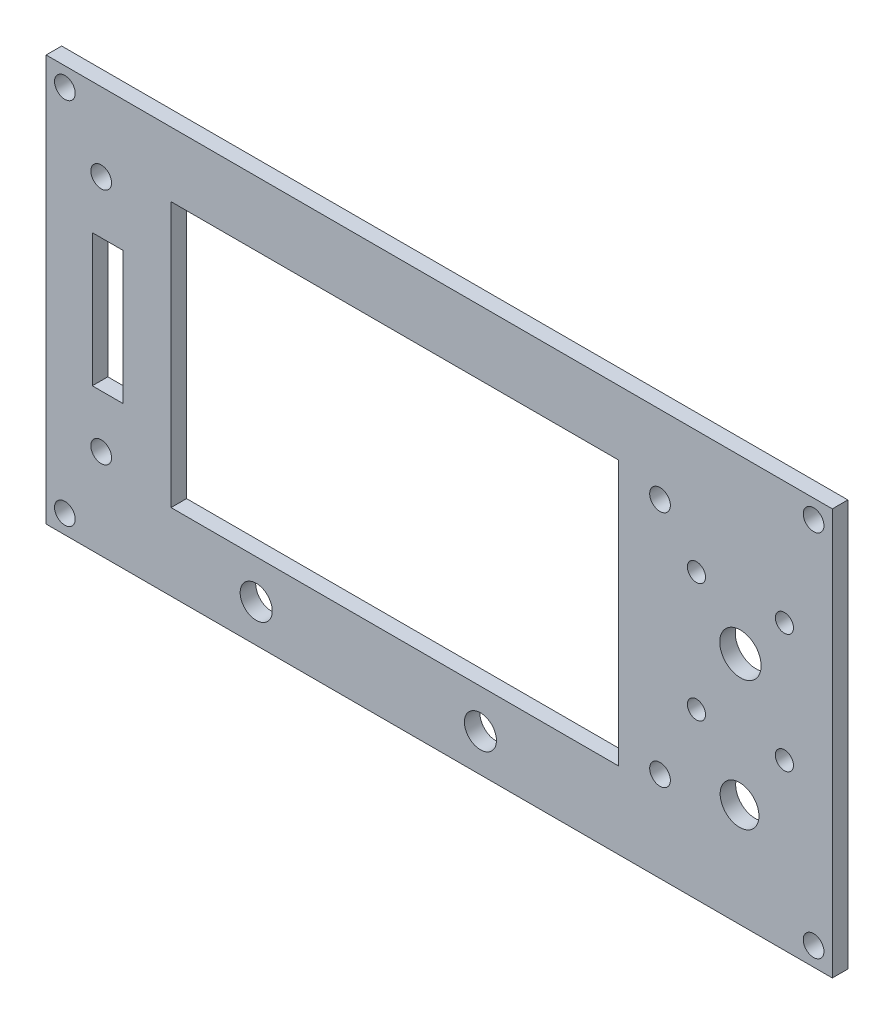
SolidWorks part; units mm, degrees
ref_plane "Plan de face" through (0, 0, 0) normal (0, 0, 1) x (1, 0, 0)
ref_plane "Plan de dessus" through (0, 0, 0) normal (0, 1, 0) x (1, 0, 0)
ref_plane "Plan de droite" through (0, 0, 0) normal (1, 0, 0) x (0, 0, -1)
sketch "Esquisse1" plane through (0, 0, -2.2) normal (0, 0, 1) x (1, 0, 0)
  line L0 (-15.1944, 26.9214) -> (-95.1944, 26.9214) construction
  line L1 (-119.8323, 39.9055) -> (32.1075, 39.9055)
  line L2 (-119.8323, 39.9055) -> (-119.8323, -38.6114)
  line L3 (-119.8323, -38.6114) -> (32.1075, -38.6114)
  line L4 (32.1075, 39.9055) -> (32.1075, -38.6114)
  line L5 (-95.6944, 27.4214) -> (-9.1944, 27.4214)
  line L6 (-95.6944, 27.4214) -> (-95.6944, -23.7786)
  line L7 (-95.6944, -23.7786) -> (-9.1944, -23.7786)
  line L8 (-9.1944, 27.4214) -> (-9.1944, -23.7786)
  line L9 (-95.1944, 26.9214) -> (-95.1944, -23.2786) construction
  line L10 (-15.1944, -23.2786) -> (-15.1944, 26.9214) construction
  line L11 (-95.1944, -23.2786) -> (-15.1944, -23.2786) construction
  line L12 (-112.5896, 39.9055) -> (-119.8323, 32.6629) construction
  line L13 (-110.9137, 14.6275) -> (-104.9761, 14.6275)
  line L14 (-110.9137, 14.6275) -> (-110.9137, -11.0054)
  line L15 (-110.9137, -11.0054) -> (-104.9761, -11.0054)
  line L16 (-104.9761, 14.6275) -> (-104.9761, -11.0054)
  line L17 (24.8649, 39.9055) -> (32.1075, 32.6629) construction
  line L18 (32.1075, -31.3687) -> (24.8649, -38.6114) construction
  line L19 (-112.5896, -38.6114) -> (-119.8323, -31.3687) construction
  circle A0 centre (-109.1944, 24.8214) radius 2
  circle A1 centre (-109.1944, -21.1786) radius 2
  circle A2 centre (-1.1944, -21.1786) radius 2
  circle A3 centre (-1.1944, 24.8214) radius 2
  circle A4 centre (-116.211, 36.2842) radius 2
  circle A5 centre (-116.211, -34.9901) radius 2
  circle A6 centre (28.4862, 36.2842) radius 2
  circle A7 centre (28.4862, -34.9901) radius 2
  circle A8 centre (14.3452, 6.7499) radius 4
  circle A9 centre (5.8452, 16.2043) radius 1.75
  circle A10 centre (22.8452, 16.2043) radius 1.75
  circle A11 centre (22.8452, -6.7957) radius 1.75
  circle A12 centre (5.8452, -6.7957) radius 1.75
  circle A13 centre (14.1766, -18.6114) radius 3.75
  circle A15 centre (-79.2375, -31.3167) radius 3.1
  circle A16 centre (-35.9056, -31.3167) radius 3.1
  circle A17 centre (-1.1944, 24.8214) radius 2 construction
  circle A18 centre (-79.2375, -31.3167) radius 3.1 construction
  circle A19 centre (-35.9056, -31.3167) radius 3.1 construction
  circle A20 centre (-1.1944, -21.1786) radius 2 construction
  circle A21 centre (-109.1944, -21.1786) radius 2 construction
  circle A22 centre (-109.1944, 24.8214) radius 2 construction
  dimension "D5" = 4
  dimension "D6" = 8
  dimension "D7" = 7.5
  dimension "D8" = 4
  dimension "D9" = 3.5
  dimension "D1" = 0.5
  dimension "D2" = 0.5
  dimension "D3" = 6
  dimension "D4" = 0.5
extrude "Boss.-Extru.1" add sketch "Esquisse1" along normal blind 3
